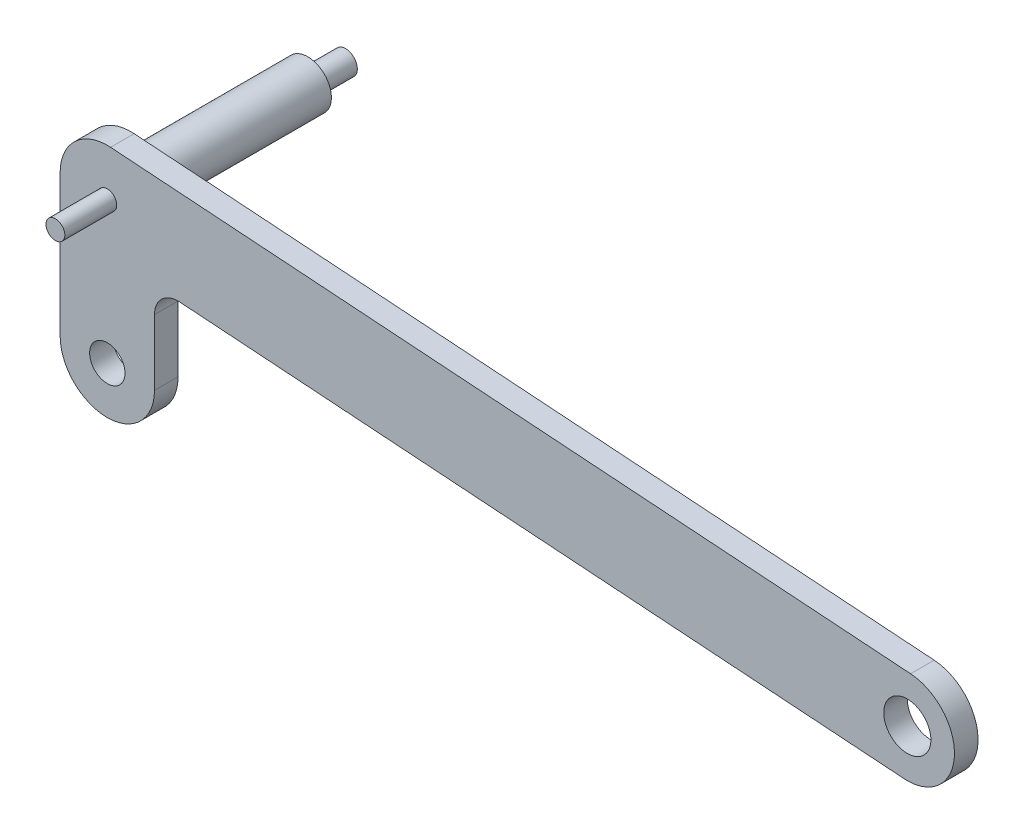
SolidWorks part; units mm, degrees
ref_plane "Alzado" through (0, 0, 0) normal (0, 0, 1) x (1, 0, 0)
ref_plane "Planta" through (0, 0, 0) normal (0, 1, 0) x (1, 0, 0)
ref_plane "Vista lateral" through (0, 0, 0) normal (1, 0, 0) x (0, 0, -1)
sketch "Croquis1" plane through (0, 0, 0) normal (0, 0, 1) x (1, 0, 0)
  line L0 (0, 0) -> (0, 60) construction
  line L1 (0, 60) -> (339.1718, 36.2828) construction
  line L2 (-20, 0) -> (-20, 60)
  line L3 (20, 0) -> (20, 27.8289)
  line L4 (-1.3951, 40.0487) -> (0, 39.9512)
  line L5 (1.3951, 79.9513) -> (340.5669, 56.2341)
  line L6 (30.6976, 37.8046) -> (337.7766, 16.3315)
  line L7 (20, 58.6015) -> (20, 60)
  line L8 (20, 78.6503) -> (20, 78.958)
  circle A0 centre (0, 0) radius 7.5
  circle A2 centre (339.1718, 36.2828) radius 10
  arc A3 (-20, 0) -> (20, 0) centre (0, 0) ccw
  arc A4 (1.3951, 79.9513) -> (-20, 60) centre (0, 60) ccw
  arc A5 (337.7766, 16.3315) -> (340.5669, 56.2341) centre (339.1718, 36.2828) ccw
  arc A6 (19.9513, 58.6049) -> (20, 60) centre (0, 60) ccw
  arc A7 (-1.3951, 40.0487) -> (0, 40) centre (0, 60) ccw
  arc A8 (30.6976, 37.8046) -> (20, 27.8289) centre (30, 27.8289) ccw
  dimension "D4" = 15
  dimension "D6" = 20
  dimension "D7" = 40
  dimension "D8" = 40
  dimension "D9" = 40
  dimension "D12" = 10
  dimension "D1" = 86
  dimension "D2" = 60
  dimension "D3" = 340
  dimension "D10" = 40
  dimension "D11" = 40
extrude "Saliente-Extruir1" add sketch "Croquis1" along normal blind 10
sketch "Croquis2" plane through (0, 0, 0) normal (0, 0, -1) x (-1, 0, 0)
  line L0 (0, 0) -> (0, 60) construction
  circle A0 centre (0, 60) radius 10
  dimension "D2" = 20
  dimension "D1" = 60
extrude "Saliente-Extruir2" add sketch "Croquis2" along normal blind 75
sketch "Croquis3" plane through (0, 0, -75) normal (0, 0, -1) x (-1, 0, 0)
  circle A0 centre (0, 60) radius 5
  dimension "D1" = 10
extrude "Saliente-Extruir3" add sketch "Croquis3" along normal blind 16
sketch "Croquis4" plane through (0, 0, 10) normal (0, 0, 1) x (1, 0, 0)
  circle A0 centre (0, 60) radius 4
  circle A1 centre (0, 60) radius 10 construction
  dimension "D1" = 8
extrude "Saliente-Extruir4" add sketch "Croquis4" along normal blind 22
